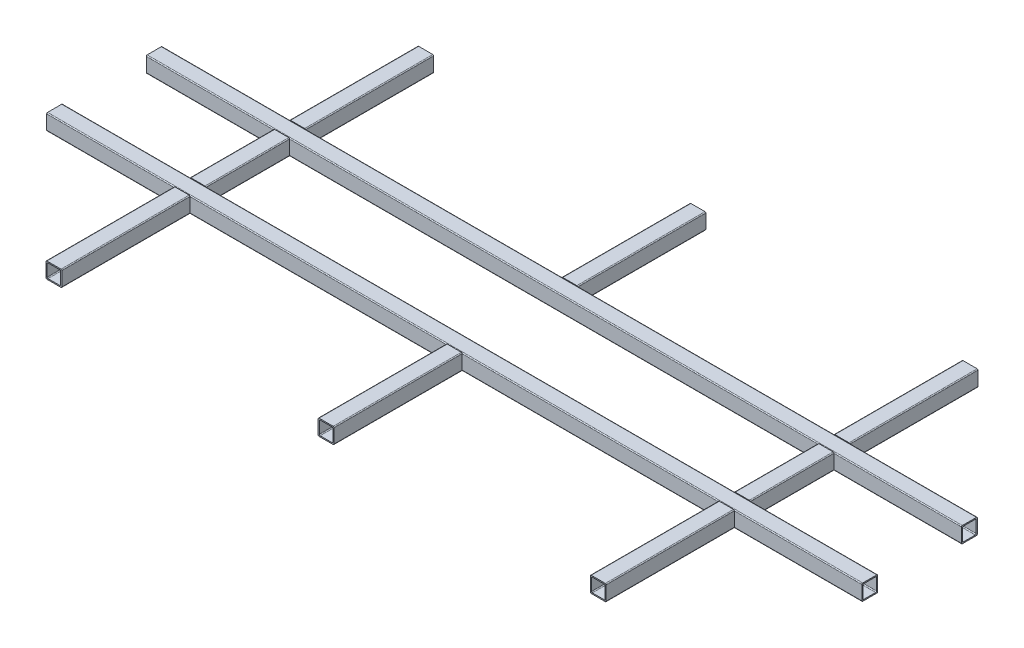
SolidWorks part; units mm, degrees
material "AISI 1020 Acier laminé à froid"
ref_plane "Plan de face" through (0, 0, 0) normal (0, 0, 1) x (1, 0, 0)
ref_plane "Plan de dessus" through (0, 0, 0) normal (0, 1, 0) x (1, 0, 0)
ref_plane "Plan de droite" through (0, 0, 0) normal (1, 0, 0) x (0, 0, -1)
sketch "Esquisse1" plane through (0, 0, 0) normal (0, 1, 0) x (1, 0, 0)
  line L0 (-900, 110) -> (900, 110)
  line L1 (-900, -110) -> (900, -110)
  line L2 (0, 110) -> (0, -110) construction
  line L4 (85, 0) -> (-85, 0) construction
  line L5 (0, 110) -> (0, 410.5)
  line L6 (-601, 110) -> (-601, 410.5)
  line L7 (601, 110) -> (601, 410.5)
  line L8 (-990, 0) -> (990, 0) construction
  line L9 (601, -110) -> (601, -410.5)
  line L10 (-601, -110) -> (-601, -410.5)
  line L11 (0, -110) -> (0, -410.5)
  line L12 (-601, 110) -> (-601, -110)
  line L13 (601, 110) -> (601, -110)
  circle A0 centre (0, 0) radius 85 construction
  point P9 (0, 0)
  point P13 (0, 0)
  point P14 (0, 110)
  dimension "D3" = 170
  dimension "D2" = 1800
  dimension "D1" = 220
  dimension "D4" = 300.5
  dimension "D5" = 601
  dimension "D6" = 601
other "Custom TUBE-CARRE-35-2.5(1)"
ref_plane "Plan2" through (-900, 0, -110) normal (1, 0, 0) x (0, 0, -1)
sketch "Esquisse14" plane through (-900, 0, -110) normal (1, 0, 0) x (0, 0, -1)
  line L1 (-13, -15) -> (13, -15)
  line L2 (-15, -13) -> (-15, 13)
  line L3 (-13, 15) -> (13, 15)
  line L4 (15, -13) -> (15, 13)
  line L5 (-15, -15) -> (15, 15) construction
  line L6 (-15, 15) -> (15, -15) construction
  line L7 (-15.5, -17.5) -> (15.5, -17.5)
  line L8 (-17.5, -15.5) -> (-17.5, 15.5)
  line L9 (-15.5, 17.5) -> (15.5, 17.5)
  line L10 (17.5, -15.5) -> (17.5, 15.5)
  line L11 (-17.5, -17.5) -> (17.5, 17.5) construction
  line L12 (-17.5, 17.5) -> (17.5, -17.5) construction
  arc A0 (15.5, -17.5) -> (17.5, -15.5) centre (15.5, -15.5) ccw
  arc A1 (13, -15) -> (15, -13) centre (13, -13) ccw
  arc A2 (-13, -15) -> (-15, -13) centre (-13, -13) cw
  arc A3 (-15.5, -17.5) -> (-17.5, -15.5) centre (-15.5, -15.5) cw
  arc A4 (15.5, 17.5) -> (17.5, 15.5) centre (15.5, 15.5) cw
  arc A5 (13, 15) -> (15, 13) centre (13, 13) cw
  arc A6 (-15, 13) -> (-13, 15) centre (-13, 13) cw
  arc A7 (-17.5, 15.5) -> (-15.5, 17.5) centre (-15.5, 15.5) cw
  point P0 (0, 0)
  point P6 (0, 0)
  point P35 (0, 17.5)
  point P36 (0, 15)
  point P37 (-15, 0)
  point P38 (-17.5, 0)
  point P39 (0, -15)
  point P40 (0, -17.5)
  point P41 (15, 0)
  point P42 (17.5, 0)
  point P43 (0, 0)
  dimension "D5" = 2
  dimension "D1" = 2.5
  dimension "D2" = 35
  dimension "D3" = 35
  dimension "D4" = 2.5
other "Custom TUBE-CARRE-35-2.5(4)"
ref_plane "Plan3" through (601, 0, 110) normal (0, 0, 1) x (1, 0, 0)
sketch "Esquisse16" plane through (601, 0, 110) normal (0, 0, 1) x (1, 0, 0)
  line L1 (-13, -15) -> (13, -15)
  line L2 (-15, -13) -> (-15, 13)
  line L3 (-13, 15) -> (13, 15)
  line L4 (15, -13) -> (15, 13)
  line L5 (-15, -15) -> (15, 15) construction
  line L6 (-15, 15) -> (15, -15) construction
  line L7 (-15.5, -17.5) -> (15.5, -17.5)
  line L8 (-17.5, -15.5) -> (-17.5, 15.5)
  line L9 (-15.5, 17.5) -> (15.5, 17.5)
  line L10 (17.5, -15.5) -> (17.5, 15.5)
  line L11 (-17.5, -17.5) -> (17.5, 17.5) construction
  line L12 (-17.5, 17.5) -> (17.5, -17.5) construction
  arc A0 (15.5, -17.5) -> (17.5, -15.5) centre (15.5, -15.5) ccw
  arc A1 (13, -15) -> (15, -13) centre (13, -13) ccw
  arc A2 (-13, -15) -> (-15, -13) centre (-13, -13) cw
  arc A3 (-15.5, -17.5) -> (-17.5, -15.5) centre (-15.5, -15.5) cw
  arc A4 (15.5, 17.5) -> (17.5, 15.5) centre (15.5, 15.5) cw
  arc A5 (13, 15) -> (15, 13) centre (13, 13) cw
  arc A6 (-15, 13) -> (-13, 15) centre (-13, 13) cw
  arc A7 (-17.5, 15.5) -> (-15.5, 17.5) centre (-15.5, 15.5) cw
  point P0 (0, 0)
  point P6 (0, 0)
  point P35 (0, 17.5)
  point P36 (0, 15)
  point P37 (-15, 0)
  point P38 (-17.5, 0)
  point P39 (0, -15)
  point P40 (0, -17.5)
  point P41 (15, 0)
  point P42 (17.5, 0)
  point P43 (0, 0)
  dimension "D5" = 2
  dimension "D1" = 2.5
  dimension "D2" = 35
  dimension "D3" = 35
  dimension "D4" = 2.5
other "Ajuster/Prolonger4"
other "Ajuster/Prolonger5"
